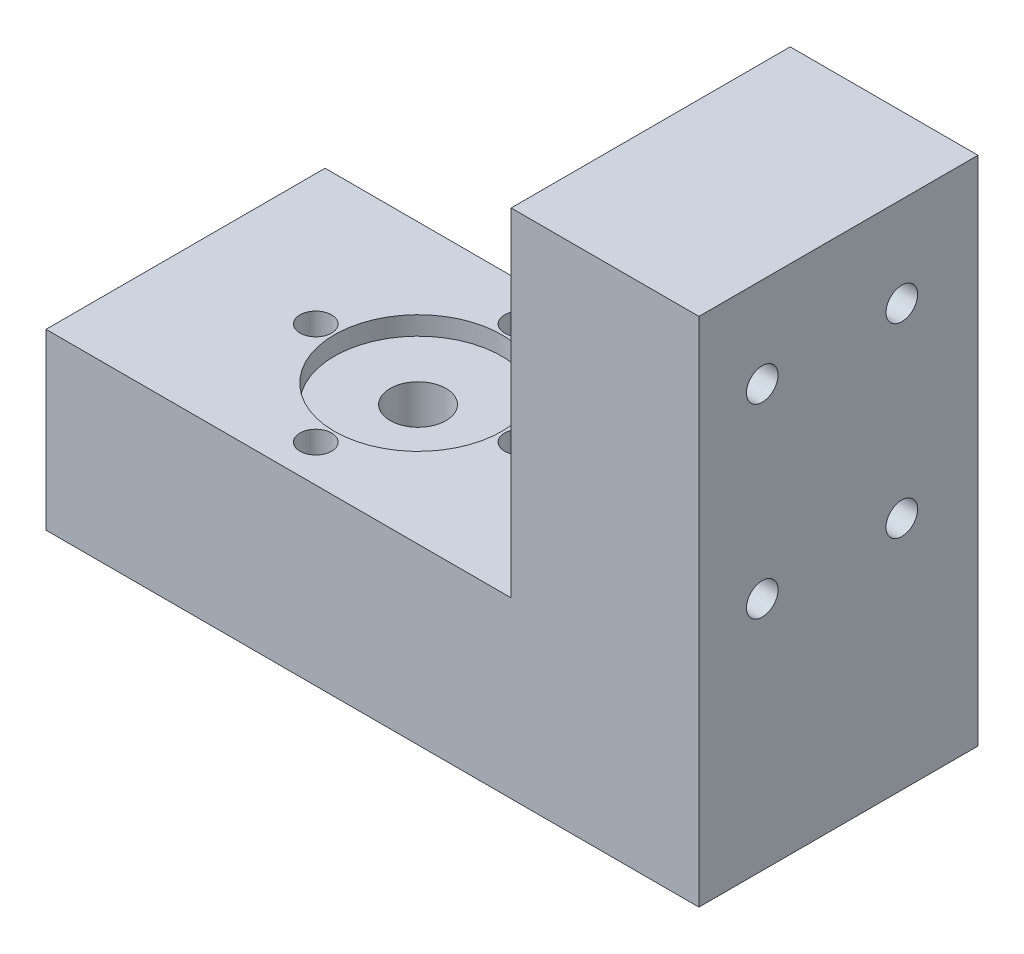
SolidWorks part; units mm, degrees
material "ABS"
ref_plane "Front Plane" through (0, 0, 0) normal (0, 0, 1) x (1, 0, 0)
ref_plane "Top Plane" through (0, 0, 0) normal (0, 1, 0) x (1, 0, 0)
ref_plane "Right Plane" through (0, 0, 0) normal (1, 0, 0) x (0, 0, -1)
sketch "Sketch1" plane through (0, 0, 0) normal (0, 0, 1) x (1, 0, 0)
  line L0 (0, 0) -> (0, 18.7)
  line L1 (0, 18.7) -> (50, 18.7)
  line L2 (50, 18.7) -> (50, 55)
  line L3 (50, 55) -> (70.19, 55)
  line L4 (70.19, 55) -> (70.19, 0)
  line L5 (70.19, 0) -> (0, 0)
  dimension "D1" = 18.7
  dimension "D2" = 50
  dimension "D3" = 20.19
  dimension "D4" = 55
extrude "Boss-Extrude1" add sketch "Sketch1" against normal blind 30
sketch "Sketch2" plane through (0, 18.7, 0) normal (0, 1, 0) x (1, 0, 0)
  line L1 (50, 0) -> (0, 0) construction
  line L3 (50, 30) -> (50, 0) construction
  circle A0 centre (25, 15) radius 9
  dimension "D1" = 18
  dimension "D2" = 15
  dimension "D3" = 25
extrude "Cut-Extrude1" cut sketch "Sketch2" against normal blind 2
sketch "Sketch4" plane through (0, 18.7, 0) normal (0, 1, 0) x (1, 0, 0)
  line L0 (0, 30) -> (0, 0) construction
  circle A0 centre (25, 15) radius 11 construction
  circle A1 centre (25, 26) radius 1.7
  circle A2 centre (36, 15) radius 1.7
  circle A3 centre (25, 4) radius 1.7
  circle A4 centre (14, 15) radius 1.7
  circle A5 centre (25, 15) radius 3
  point P15 (25, 15)
  dimension "D3" = 25
  dimension "D1" = 22
  dimension "D2" = 3.4
  dimension "D5" = 6
  dimension "D4" = 4
extrude "Cut-Extrude2" cut sketch "Sketch4" against normal through all
sketch "Sketch5" plane through (70.19, 0, 0) normal (1, 0, 0) x (0, 0, -1)
  circle A0 centre (6.8105, 45.304) radius 1.7
  circle A1 centre (6.8105, 25.304) radius 1.7
  circle A2 centre (21.8105, 45.304) radius 1.7
  circle A3 centre (21.8105, 25.304) radius 1.7
  dimension "D2" = 3.4
  dimension "D1" = 3.4
  dimension "D3" = 3.4
  dimension "D4" = 3.4
  dimension "D5" = 20
  dimension "D6" = 15
extrude "Cut-Extrude3" cut sketch "Sketch5" against normal through all
equation "\"F1L\"= 50'Feature 1 Length"
equation "\"F1H\"= 18.7'Feature 1 Height"
equation "\"F2L\"= 55'Feature 2 Length"
equation "\"F2H\"= 20.19'Feature 2 Height"
equation "\"D1@Sketch1\"=\"F1H\""
equation "\"D2@Sketch1\"=\"F1L\""
equation "\"D3@Sketch1\"=\"F2H\""
equation "\"CD\"= 3.4'Circles Diameter"
equation "\"E\"= 30'Extrusion"
equation "\"D2@Sketch2\"=\"E\"/2"
equation "\"D3@Sketch2\"=\"F1L\"/2"
equation "\"D1@Boss-Extrude1\"=\"E\""
equation "\"D2@Sketch4\"=\"CD\""
equation "\"D3@Sketch4\"=\"F1L\"/2"
equation "\"D1@Sketch5\"=\"CD\""
equation "\"D2@Sketch5\"=\"CD\""
equation "\"D3@Sketch5\"=\"CD\""
equation "\"D4@Sketch5\"=\"CD\""
equation "\"D6@Sketch5\"=\"E\"/2"
